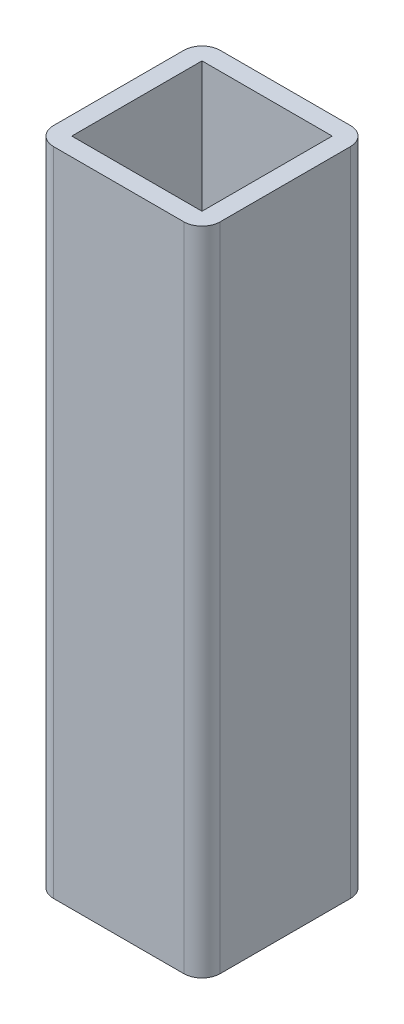
SolidWorks part; units mm, degrees
ref_plane "Front Plane" through (0, 0, 0) normal (0, 0, 1) x (1, 0, 0)
ref_plane "Top Plane" through (0, 0, 0) normal (0, 1, 0) x (1, 0, 0)
ref_plane "Right Plane" through (0, 0, 0) normal (1, 0, 0) x (0, 0, -1)
sketch "Sketch1" plane through (0, 0, 0) normal (0, 1, 0) x (1, 0, 0)
  line L1 (2.8, 0) -> (22.8, 0)
  line L2 (0, -2.8) -> (0, -22.8)
  line L3 (2.8, -25.6) -> (22.8, -25.6)
  line L4 (25.6, -2.8) -> (25.6, -22.8)
  arc A0 (22.8, 0) -> (25.6, -2.8) centre (22.8, -2.8) cw
  arc A1 (22.8, -25.6) -> (25.6, -22.8) centre (22.8, -22.8) ccw
  arc A2 (0, -22.8) -> (2.8, -25.6) centre (2.8, -22.8) ccw
  arc A3 (2.8, 0) -> (0, -2.8) centre (2.8, -2.8) ccw
  point P7 (25.6, 0)
  point P10 (25.6, -25.6)
  point P15 (0, 0)
  dimension "D2" = 2.8
  dimension "D1" = 25.6
extrude "Boss-Extrude1" add sketch "Sketch1" along normal blind 100
sketch "Sketch3" plane through (0, 0, 0) normal (0, -1, 0) x (-1, 0, 0)
  line L4 (-2.8, -2.8) -> (-22.8, -2.8)
  line L5 (-2.8, -2.8) -> (-2.8, -22.8)
  line L6 (-2.8, -22.8) -> (-22.8, -22.8)
  line L7 (-22.8, -2.8) -> (-22.8, -22.8)
  line L8 (-2.8, -2.8) -> (-22.8, -22.8) construction
  line L9 (-2.8, -22.8) -> (-22.8, -2.8) construction
  point P6 (-12.8, -12.8)
extrude "Cut-Extrude1" cut sketch "Sketch3" against normal blind 1040.5
